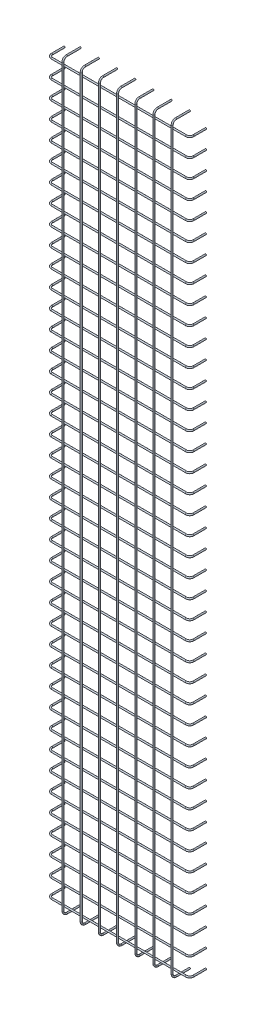
SolidWorks part; units mm, degrees
material "AISI 1020"
ref_plane "Спереди" through (0, 0, 0) normal (0, 0, 1) x (1, 0, 0)
ref_plane "Сверху" through (0, 0, 0) normal (0, 1, 0) x (1, 0, 0)
ref_plane "Справа" through (0, 0, 0) normal (1, 0, 0) x (0, 0, -1)
sketch "Эскиз1" plane through (0, 0, 0) normal (1, 0, 0) x (0, 0, -1)
  line L0 (50, 1020.5) -> (12, 1020.5)
  line L1 (2, 1010.5) -> (2, -1010.5)
  line L2 (12, -1020.5) -> (50, -1020.5)
  line L3 (0, 1022.5) -> (0, -1022.5) construction
  line L4 (47, 1022.5) -> (3, 1022.5) construction
  line L5 (50, 1022.5) -> (50, -1022.5) construction
  arc A0 (2, -1010.5) -> (12, -1020.5) centre (12, -1010.5) ccw
  arc A1 (12, 1020.5) -> (2, 1010.5) centre (12, 1010.5) ccw
  point P2 (0, 0)
  point P9 (0, 0)
  point P12 (2, 0)
  dimension "D3" = 10
  dimension "D1" = 2
  dimension "D2" = 2
sketch "Эскиз2" plane through (0, 0, -50) normal (0, 0, -1) x (-1, 0, 0)
  line L1 (0, -1010.5) -> (0, -1020.5) construction
  circle A0 centre (0, -1020.5) radius 2
  point P1 (0, 0)
  dimension "D1" = 4
sweep "По траектории1" add profiles "Эскиз2" path "Эскиз1"
pattern_linear "Линейный массив2" count 4 spacing 50 along (-1, 0, 0) of bodies 103
pattern_linear "Линейный массив3" count 4 spacing 50 along (1, 0, 0) of bodies 103
sketch "Эскиз3" plane through (0, 0, 0) normal (0, 1, 0) x (1, 0, 0)
  line L0 (-194.25, 50) -> (-194.25, 16)
  line L1 (-184.25, 6) -> (184.25, 6)
  line L2 (194.25, 16) -> (194.25, 50)
  line L3 (246.25, 50) -> (-246.25, 50) construction
  line L4 (196.25, 3) -> (196.25, 47) construction
  line L5 (-196.25, 47) -> (-196.25, 3) construction
  circle A0 centre (150, 2) radius 2 construction
  arc A1 (184.25, 6) -> (194.25, 16) centre (184.25, 16) ccw
  arc A2 (-194.25, 16) -> (-184.25, 6) centre (-184.25, 16) ccw
  point P2 (0, 0)
  point P7 (0, 0)
  point P8 (170.151, 7.039)
  dimension "D1" = 4
  dimension "D4" = 10
  dimension "D2" = 2
  dimension "D3" = 2
sketch "Эскиз4" plane through (0, 0, -50) normal (0, 0, -1) x (-1, 0, 0)
  circle A0 centre (-194.25, 0) radius 2
  dimension "D1" = 4
sweep "По траектории2" add profiles "Эскиз4" path "Эскиз3"
pattern_linear "Линейный массив4" count 21 spacing 50 along (0, 1, 0) of bodies 110
pattern_linear "Линейный массив5" count 21 spacing 50 along (0, -1, 0) of bodies 110
